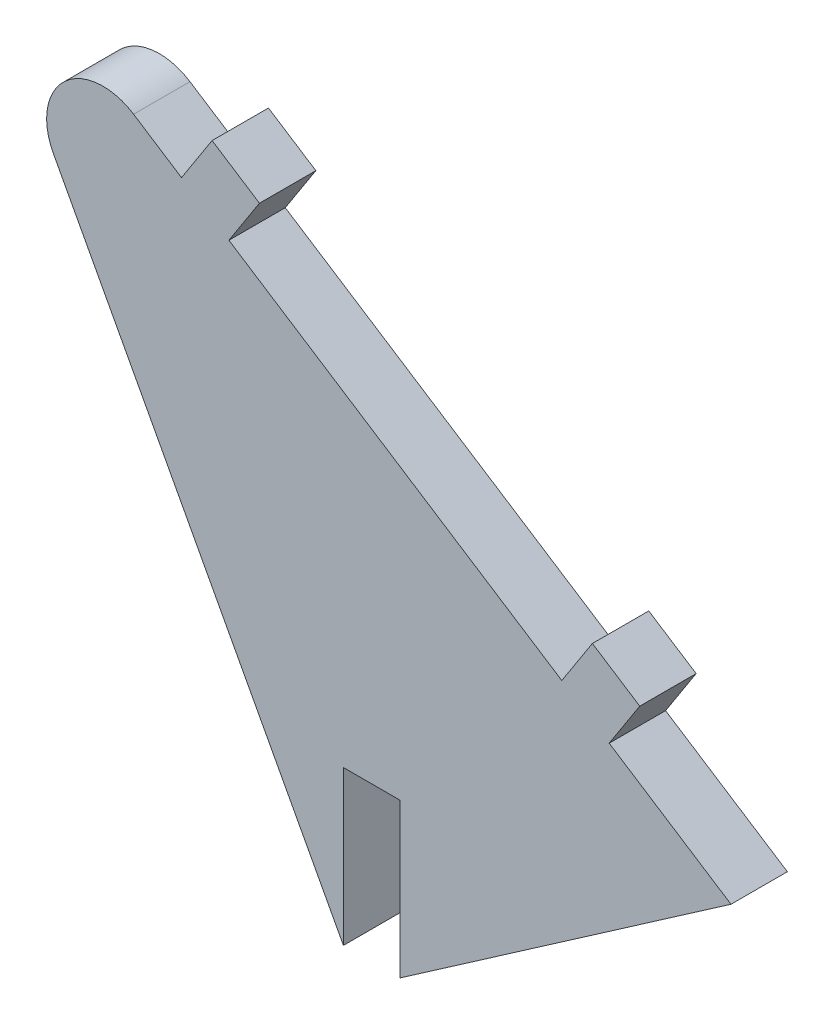
SolidWorks part; units mm, degrees
ref_plane "Front Plane" through (0, 0, 0) normal (0, 0, 1) x (1, 0, 0)
ref_plane "Top Plane" through (0, 0, 0) normal (0, 1, 0) x (1, 0, 0)
ref_plane "Right Plane" through (0, 0, 0) normal (1, 0, 0) x (0, 0, -1)
sketch "Sketch1" plane through (0, 0, 0) normal (0, 0, 1) x (1, 0, 0)
  line L0 (0, 73.1433) -> (1.524, 73.1433)
  line L1 (1.524, 73.1433) -> (0, 73.1433) construction
  line L2 (1.524, 73.1433) -> (1.524, 68.9786)
  line L3 (1.524, 68.9786) -> (10.4748, 75.1796)
  line L4 (-10.6288, 88.7977) -> (-4.3754, 84.7624)
  line L5 (-3.5491, 86.043) -> (-2.2686, 85.2166)
  line L6 (0, 68.9786) -> (-10.6288, 88.7977)
  line L7 (-3.0949, 83.9361) -> (5.9025, 78.1301)
  line L8 (0, 73.1433) -> (0, 68.9786)
  line L9 (7.183, 77.3038) -> (8.0094, 78.5843)
  line L10 (5.9025, 78.1301) -> (6.7288, 79.4107)
  line L12 (8.0094, 78.5843) -> (6.7288, 79.4107)
  line L13 (7.183, 77.3038) -> (10.4748, 75.1796)
  line L14 (-3.0949, 83.9361) -> (-2.2686, 85.2166)
  line L15 (-4.3754, 84.7624) -> (-3.5491, 86.043)
  point P15 (0.762, 73.1433)
  dimension "D1" = 10.708
  dimension "D2" = 1.524
  dimension "D3" = 1.524
extrude "Boss-Extrude1" add sketch "Sketch1" along normal blind 1.524
fillet "Fillet1" radius 1.524 1 edges at (-10.6288, 88.7977, 0.762)
